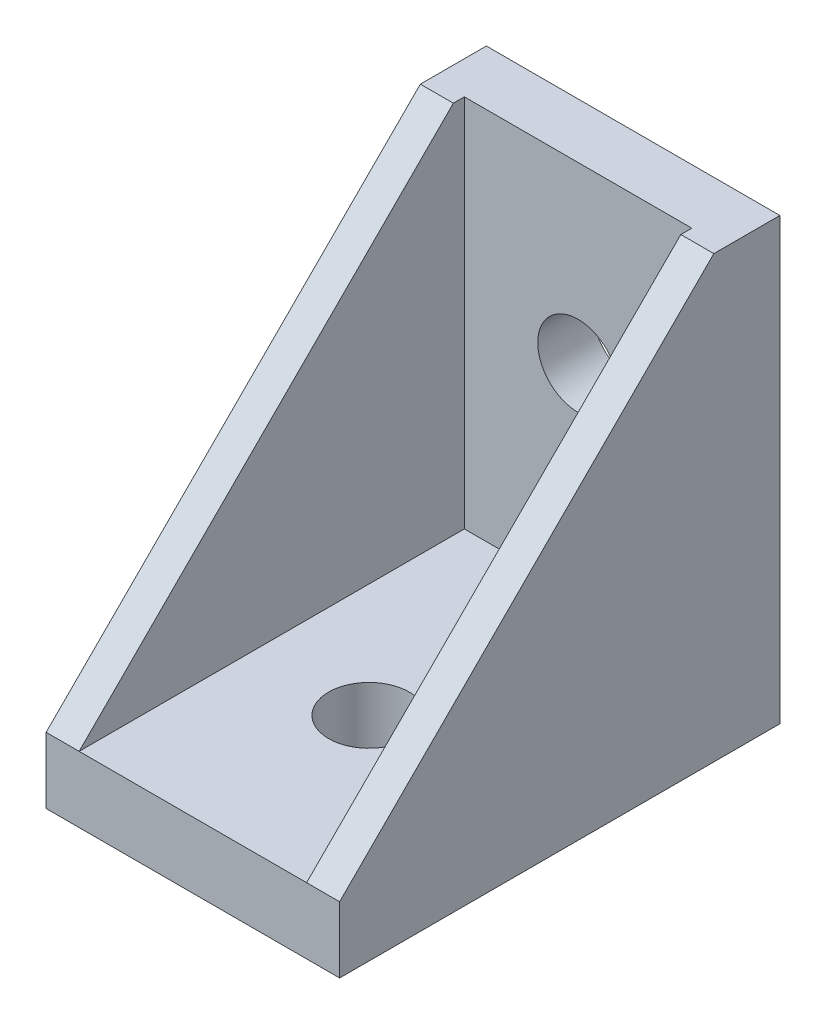
SolidWorks part; units mm, degrees
material "5052-H36"
ref_plane "Front Plane" through (0, 0, 0) normal (0, 0, 1) x (1, 0, 0)
ref_plane "Top Plane" through (0, 0, 0) normal (0, 1, 0) x (1, 0, 0)
ref_plane "Right Plane" through (0, 0, 0) normal (1, 0, 0) x (0, 0, -1)
sketch "Sketch1" plane through (0, 0, 0) normal (1, 0, 0) x (0, 0, -1)
  line L0 (-78.5156, 0) -> (78.5156, 0) construction
  line L1 (0, -57.3869) -> (0, 57.3869) construction
  line L2 (-15, 0) -> (15, 0)
  line L3 (15, 0) -> (15, 30)
  line L4 (15, 30) -> (10.5, 30)
  line L5 (-15, 0) -> (-15, 4.5)
  line L6 (-15, 4.5) -> (10.5, 30)
  point P4 (0, 0)
  point P8 (0, 0)
  point P11 (0, 0)
  dimension "D1" = 30
  dimension "D2" = 30
  dimension "D3" = 4.5
  dimension "D4" = 4.5
extrude "Boss-Extrude1" add sketch "Sketch1" along normal mid plane 20
sketch "Sketch2" plane through (0, 0, 0) normal (1, 0, 0) x (0, 0, -1)
  line L0 (-53.718, 0) -> (53.718, 0) construction
  line L2 (0, -65.0864) -> (0, 65.0864) construction
  line L3 (-11.25, 4.5) -> (11.25, 4.5)
  line L4 (11.25, 4.5) -> (11.25, 26.1293)
  line L5 (11.25, 26.1293) -> (11.25, 30)
  line L7 (15, 30) -> (10.5, 30) construction
  line L8 (11.25, 30) -> (10.5, 30)
  line L9 (10.5, 30) -> (-15, 4.5)
  line L10 (-15, 4.5) -> (-11.25, 4.5)
  point P4 (0, 0)
  point P8 (0, 0)
  point P11 (0, 4.5)
  dimension "D1" = 4.5
  dimension "D2" = 22.5
extrude "Cut-Extrude1" cut sketch "Sketch2" against normal mid plane 15.5
sketch "Sketch3" plane through (0, 0, -11.25) normal (0, 0, 1) x (1, 0, 0)
  line L0 (-27.2492, 0) -> (27.2492, 0) construction
  line L1 (0, -38.1637) -> (0, 38.1637) construction
  circle A0 centre (0, 18) radius 2.75
  point P4 (0, 0)
  point P8 (0, 0)
  dimension "D1" = 18
  dimension "D2" = 5.5
extrude "Cut-Extrude2" cut sketch "Sketch3" against normal blind 15.5
sketch "Sketch4" plane through (0, 4.5, 0) normal (0, 1, 0) x (1, 0, 0)
  line L0 (-32.2614, 0) -> (32.2614, 0) construction
  line L1 (0, -30.608) -> (0, 30.608) construction
  line L3 (10, 15) -> (-10, 15) construction
  circle A0 centre (0, -3) radius 2.75
  circle A1 centre (0, 5) radius 2.6
  point P4 (0, 0)
  point P8 (0, 0)
  dimension "D1" = 5.5
  dimension "D2" = 18
  dimension "D3" = 10
  dimension "D4" = 5.2
extrude "Cut-Extrude3" cut sketch "Sketch4" against normal blind 15.5 contours A0
